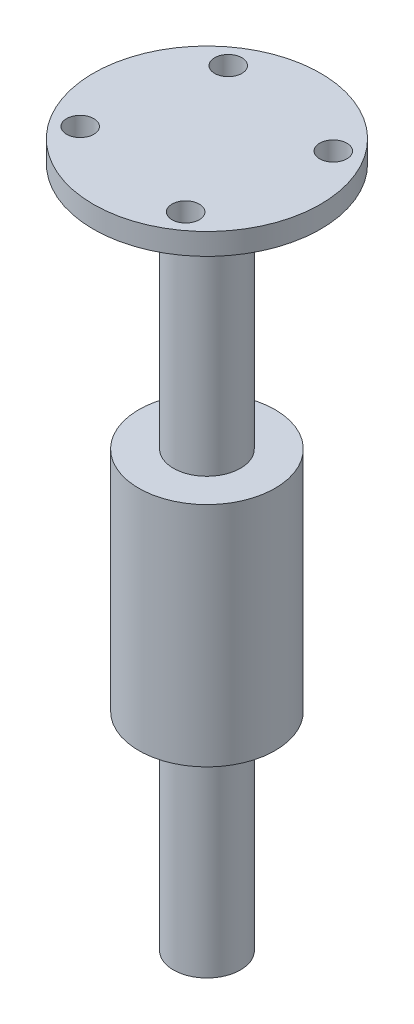
SolidWorks part; units mm, degrees
ref_plane "Plan de face" through (0, 0, 0) normal (0, 0, 1) x (1, 0, 0)
ref_plane "Plan de dessus" through (0, 0, 0) normal (0, 1, 0) x (1, 0, 0)
ref_plane "Plan de droite" through (0, 0, 0) normal (1, 0, 0) x (0, 0, -1)
sketch "Esquisse1" plane through (0, 0, 0) normal (0, 1, 0) x (1, 0, 0)
  circle A0 centre (0, 0) radius 2.95
extrude "Boss.-Extru.1" add sketch "Esquisse1" along normal blind 60
sketch "Esquisse2" plane through (0, 60, 0) normal (0, 1, 0) x (1, 0, 0)
  circle A0 centre (0, 0) radius 10
extrude "Boss.-Extru.2" add sketch "Esquisse2" along normal blind 3
sketch "Esquisse3" plane through (0, 63, 0) normal (0, 1, 0) x (1, 0, 0)
  line L0 (-5.8016, 8.145) -> (5.8016, -8.145)
  line L1 (5.8016, -8.145) -> (-8.145, -5.8016)
  line L2 (-8.145, -5.8016) -> (8.145, 5.8016)
  line L3 (8.145, 5.8016) -> (-5.8016, 8.145)
  line L4 (-8.145, -5.8016) -> (-5.8016, 8.145)
  line L5 (5.8016, -8.145) -> (8.145, 5.8016)
  line L6 (-8.145, -5.8016) -> (-6.516, -4.6413)
  line L7 (-5.8016, 8.145) -> (-4.6413, 6.516)
  line L8 (8.145, 5.8016) -> (6.4958, 4.6269)
  line L9 (5.8016, -8.145) -> (4.6413, -6.516)
  circle A0 centre (0, 0) radius 10 construction
  circle A1 centre (-6.516, -4.6413) radius 1.2
  circle A2 centre (-4.6413, 6.516) radius 1.2
  circle A3 centre (6.4958, 4.6269) radius 1.2
  circle A4 centre (4.6413, -6.516) radius 1.2
extrude "Enlèv. mat.-Extru.1" cut sketch "Esquisse3" against normal blind 10 contours L2 A1 L6 | L7 A2 L0 | L6 A1 L2 | L0 A4 | L0 A4 | A3
sketch "Esquisse4" plane through (0, 63, 0) normal (0, 1, 0) x (1, 0, 0)
  circle A0 centre (4.6413, -6.516) radius 1.2
  circle A1 centre (-6.516, -4.6413) radius 1.2
  circle A2 centre (6.4958, 4.6269) radius 1.2
  circle A3 centre (-4.6413, 6.516) radius 1.2
  circle A4 centre (0, 0) radius 10
extrude "Enlèv. mat.-Extru.2" cut sketch "Esquisse4" against normal blind 1.1
ref_plane "Plan1" through (0, 38.25, 0) normal (0, -1, 0) x (-1, 0, 0)
sketch "Esquisse5" plane through (0, 38.25, 0) normal (0, -1, 0) x (-1, 0, 0)
  circle A0 centre (0, 0) radius 6
extrude "Boss.-Extru.3" add sketch "Esquisse5" along normal blind 20
